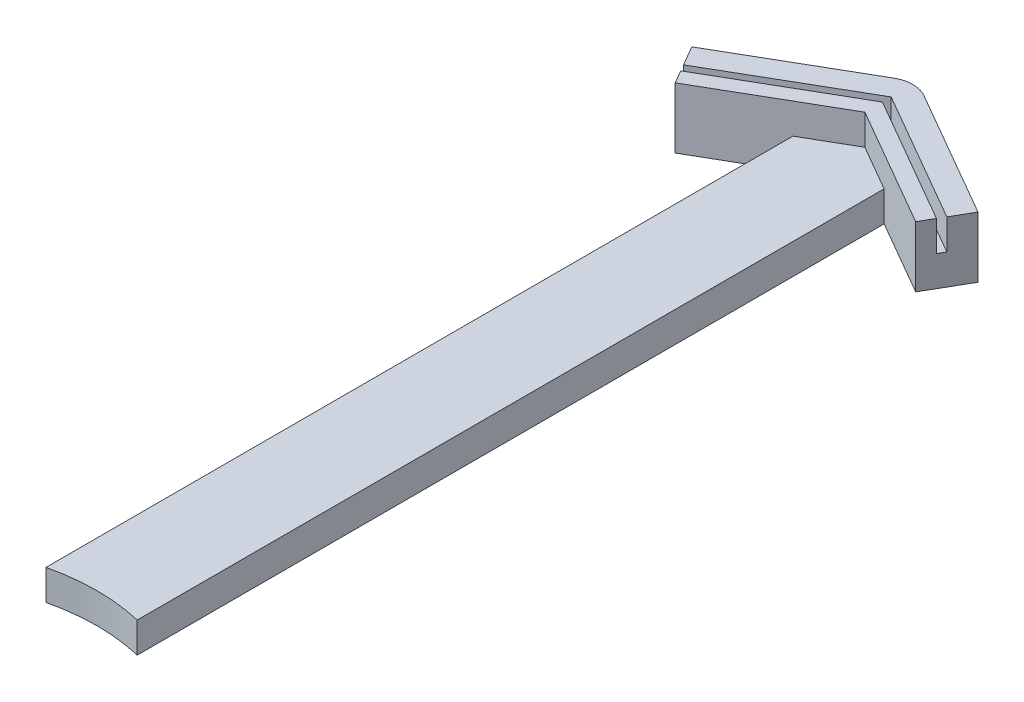
SolidWorks part; units mm, degrees
ref_plane "Front Plane" through (0, 0, 0) normal (0, 0, 1) x (1, 0, 0)
ref_plane "Top Plane" through (0, 0, 0) normal (0, 1, 0) x (1, 0, 0)
ref_plane "Right Plane" through (0, 0, 0) normal (1, 0, 0) x (0, 0, -1)
sketch "Sketch1" plane through (0, 0, 0) normal (0, 1, 0) x (1, 0, 0)
  line L0 (-91.3757, 0) -> (98.8396, 0) construction
  line L1 (0, -87.983) -> (0, 60.8417) construction
  line L2 (10, -5.7735) -> (94.1028, -54.3303)
  line L3 (-10, -5.7735) -> (-94.1028, -54.3303)
  line L4 (-94.1028, -54.3303) -> (-79.1028, -80.311)
  line L5 (-79.1028, -80.311) -> (0, -34.641)
  line L6 (0, -34.641) -> (79.1028, -80.311)
  line L7 (79.1028, -80.311) -> (94.1028, -54.3303)
  arc A0 (10, -5.7735) -> (-10, -5.7735) centre (0, -23.094) ccw
  point P13 (0, 0)
  dimension "D4" = 20
  dimension "D1" = 120
  dimension "D2" = 30
  dimension "D3" = 91.34
extrude "Boss-Extrude1" add sketch "Sketch1" along normal blind 40
sketch "Sketch2" plane through (0, 40, 0) normal (0, 1, 0) x (1, 0, 0)
  line L3 (-86.6028, -67.3206) -> (0, -17.3205)
  line L4 (0, -17.3205) -> (86.6028, -67.3206)
  line L5 (0, -23.094) -> (84.1028, -71.6508)
  line L6 (-84.1028, -71.6508) -> (0, -23.094)
  line L7 (0, -23.094) -> (84.1028, -71.6508)
  line L8 (-84.1028, -71.6508) -> (0, -23.094)
  line L9 (-84.1028, -71.6508) -> (-86.6028, -67.3206)
  line L10 (84.1028, -71.6508) -> (86.6028, -67.3206)
  dimension "D1" = 10
  dimension "D2" = 5
extrude "Cut-Extrude1" cut sketch "Sketch2" against normal blind 20
sketch "Sketch3" plane through (0, 0, 0) normal (0, -1, 0) x (1, 0, 0)
  line L0 (-79.1028, 80.311) -> (0, 34.641) construction
  line L1 (0, 34.641) -> (79.1028, 80.311) construction
  line L2 (-30, 51.9615) -> (0, 34.641)
  line L3 (0, 34.641) -> (30, 51.9615)
  line L4 (79.1028, 80.311) -> (79.1028, 532.7163) construction
  line L5 (-79.1028, 80.311) -> (-79.1028, 566.5626) construction
  line L6 (0, -258.5531) -> (0, 789.5777) construction
  line L7 (0, 34.641) -> (951.1325, 583.7776) construction
  line L8 (275, 193.4123) -> (0, 669.7263) construction
  line L9 (-30, 51.9615) -> (-30, 543.2352)
  line L10 (30, 51.9615) -> (30, 543.2352)
  line L11 (79.1028, 532.7163) -> (79.1028, 566.5626) construction
  line L12 (30, 51.9615) -> (79.1028, 80.311) construction
  line L13 (-79.1028, 80.311) -> (-30, 51.9615) construction
  arc A0 (-30, 543.2352) -> (30, 543.2352) centre (0, 669.7263) ccw
  arc A1 (0, 799.7263) -> (-79.1028, 566.5626) centre (0, 669.7263) ccw construction
  arc A2 (79.1028, 566.5626) -> (0, 799.7263) centre (0, 669.7263) ccw construction
  arc A3 (-79.1028, 566.5626) -> (-30, 543.2352) centre (0, 669.7263) ccw construction
  arc A4 (65, 557.143) -> (79.1028, 566.5626) centre (0, 669.7263) ccw construction
  arc A5 (30, 543.2352) -> (65, 557.143) centre (0, 669.7263) ccw construction
  dimension "D1" = 260
  dimension "D2" = 550
  dimension "D3" = 60
extrude "Boss-Extrude2" add sketch "Sketch3" against normal blind 20 separate body
